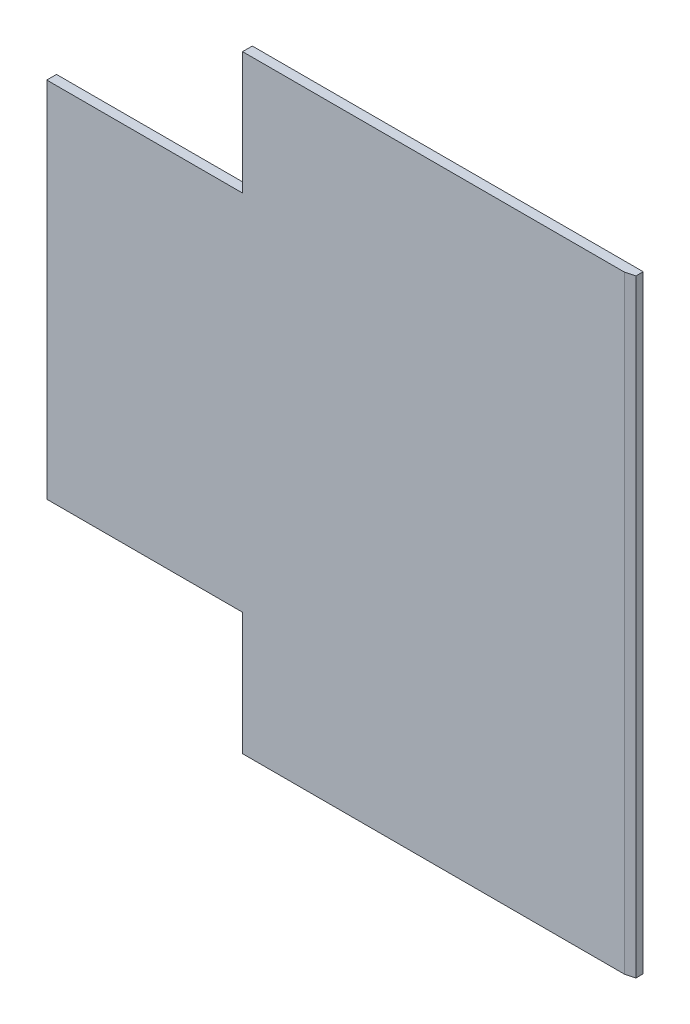
SolidWorks part; units mm, degrees
ref_plane "Alzado" through (0, 0, 0) normal (0, 0, 1) x (1, 0, 0)
ref_plane "Planta" through (0, 0, 0) normal (0, 1, 0) x (1, 0, 0)
ref_plane "Vista lateral" through (0, 0, 0) normal (1, 0, 0) x (0, 0, -1)
sketch "Sketch1" plane through (0, 0, 0) normal (0, 1, 0) x (1, 0, 0)
  line L0 (0, 0) -> (79.31, 0)
  line L1 (79.31, 0) -> (79.31, 3.17)
  line L2 (79.31, 3.17) -> (0, 3.17)
  line L3 (0, 3.17) -> (0, 0)
  dimension "D1" = 79.31
  dimension "D2" = 3.17
extrude "Boss-Extrude1" add sketch "Sketch1" along normal blind 198
sketch "Sketch2" plane through (0, 0, 0) normal (-1, 0, 0) x (0, 0, 1)
  line L10 (0, 39.89) -> (-3.17, 39.89)
  line L11 (0, 39.89) -> (0, 158.11)
  line L12 (0, 158.11) -> (-3.17, 158.11)
  line L13 (-3.17, 39.89) -> (-3.17, 158.11)
extrude "Boss-Extrude2" add sketch "Sketch2" along normal blind 63.76
sketch "Sketch3" plane through (79.31, 0, 0) normal (1, 0, 0) x (0, 0, -1)
  line L1 (3.17, 0) -> (0, 0)
  line L2 (3.17, 0) -> (3.17, 198)
  line L3 (3.17, 198) -> (0, 198)
  line L4 (0, 0) -> (0, 198)
extrude "Boss-Extrude3" add sketch "Sketch3" along normal blind 48
sketch "Sketch5" plane through (0, 198, 0) normal (0, 1, 0) x (1, 0, 0)
  line L0 (124.3014, 0) -> (127.3325, 0.8103)
  line L1 (124.3014, 0) -> (127.3325, 0)
  line L2 (127.3325, 0) -> (127.3325, 0.8103)
  point P2 (127.3325, 0)
extrude "Cut-Extrude1" cut sketch "Sketch5" against normal blind 200 contours L1 L2 L0
